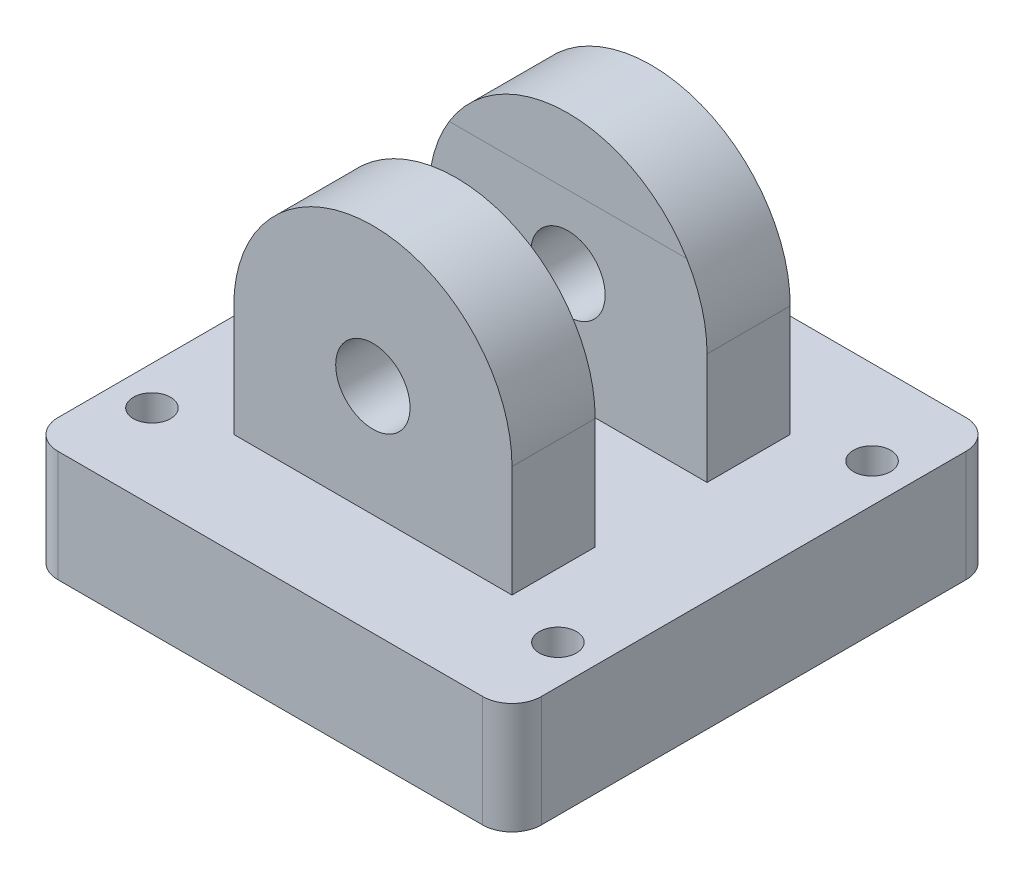
SolidWorks part; units mm, degrees
ref_plane "Front Plane" through (0, 0, 0) normal (0, 0, 1) x (1, 0, 0)
ref_plane "Top Plane" through (0, 0, 0) normal (0, 1, 0) x (1, 0, 0)
ref_plane "Right Plane" through (0, 0, 0) normal (1, 0, 0) x (0, 0, -1)
sketch "Sketch1" plane through (0, 0, 0) normal (0, 1, 0) x (1, 0, 0)
  line L1 (-82.5, 82.5) -> (82.5, 82.5)
  line L2 (-82.5, 82.5) -> (-82.5, -82.5)
  line L3 (-82.5, -82.5) -> (82.5, -82.5)
  line L4 (82.5, 82.5) -> (82.5, -82.5)
  line L5 (-82.5, 82.5) -> (82.5, -82.5) construction
  line L6 (-82.5, -82.5) -> (82.5, 82.5) construction
  point P0 (0, 0)
extrude "Boss-Extrude1" add sketch "Sketch1" along normal blind 38
sketch "Sketch2" plane through (0, 38, 0) normal (0, 1, 0) x (1, 0, 0)
  line L1 (-47.5, 47.5) -> (47.5, 47.5)
  line L2 (-47.5, 47.5) -> (-47.5, -47.5)
  line L3 (-47.5, -47.5) -> (47.5, -47.5)
  line L4 (47.5, 47.5) -> (47.5, -47.5)
  line L5 (-47.5, 47.5) -> (47.5, -47.5) construction
  line L6 (-47.5, -47.5) -> (47.5, 47.5) construction
  point P0 (0, 0)
extrude "Boss-Extrude2" add sketch "Sketch2" along normal blind 38
sketch "Sketch3" plane through (0, 0, -47.5) normal (0, 0, -1) x (-1, 0, 0)
  line L0 (-47.5, 76) -> (47.5, 76)
  arc A0 (-47.5, 76) -> (47.5, 76) centre (0, 76) cw
extrude "Boss-Extrude4" add sketch "Sketch3" against normal blind 95
sketch "Sketch5" plane through (0, 0, -47.5) normal (0, 0, -1) x (-1, 0, 0)
  circle A0 centre (0, 76) radius 12.7
extrude "Cut-Extrude1" cut sketch "Sketch5" against normal through all
sketch "Sketch7" plane through (47.5, 0, 0) normal (1, 0, 0) x (0, 0, -1)
  line L0 (0, 38) -> (19, 38)
  line L1 (-82.5, 38) -> (82.5, 38) construction
  line L2 (-47.5, 38) -> (47.5, 38) construction
sketch "Sketch8" plane through (82.5, 0, 0) normal (1, 0, 0) x (0, 0, -1)
  line L0 (19.102, 38) -> (19.102, 100.7488)
  line L1 (-82.5, 38) -> (82.5, 38) construction
  line L2 (19.102, 100.7488) -> (19.102, 123.5)
  line L3 (47.5, 123.5) -> (-47.5, 123.5) construction
  line L4 (19.102, 123.5) -> (19, 123.5)
  line L5 (19, 123.5) -> (-19, 123.5)
  line L6 (0, 123.5) -> (0, 38) construction
  line L7 (-19.102, 100.7488) -> (-19.102, 123.5)
  line L8 (-19.102, 38) -> (-19.102, 100.7488)
  line L9 (-19.102, 38) -> (19.102, 38)
extrude "Cut-Extrude2" cut sketch "Sketch8" against normal through all and the other way through all
fillet "Fillet1" radius 10 1 edges at (82.5, 19, 82.5)
fillet "Fillet2" radius 10 3 edges at (-82.5, 19, 82.5) (-82.5, 19, -82.5) (82.5, 19, -82.5)
sketch "Sketch9" plane through (0, 0, 0) normal (0, -1, 0) x (1, 0, 0)
  circle A0 centre (0, 0) radius 26
extrude "Cut-Extrude3" cut sketch "Sketch9" against normal blind 36.83
sketch "Sketch10" plane through (0, 0, 0) normal (0, -1, 0) x (1, 0, 0)
  circle A0 centre (0, 0) radius 69.85
  circle A1 centre (0, 0) radius 76.2
extrude "Cut-Extrude4" cut sketch "Sketch10" against normal blind 10
sketch "Sketch11" plane through (0, 0, -82.5) normal (0, 0, -1) x (-1, 0, 0)
  line L0 (-72.5, 19) -> (69.584, 19) construction
  line L1 (-72.5, 38) -> (-72.5, 0) construction
hole_wizard "1/2-14 NPSM Tapped Hole1" positions "3DSketch1" profile "Sketch12" tap size "1/2-14 NPSM" standard "ANSI Inch"
sketch3d "3DSketch1"
  line L0 (72.5, 19, -82.5) -> (-69.584, 19, -82.5) construction
  point P0 (-0.9389, 19, -82.5)
sketch "Sketch12" plane through (-0.9389, 19, -82.5) normal (1, 0, 0) x (0, 1, 0)
  line L0 (0, 0) -> (0, 69.2003)
  line L1 (0, 69.2003) -> (9.4869, 63.5)
  line L2 (9.4869, 63.5) -> (9.4869, 1.6002)
  line L3 (9.4869, 1.6002) -> (11.0871, 0)
  line L5 (11.0871, 0) -> (0, 0)
  line L6 (-9.4869, 1.6002) -> (-11.0871, 0) construction
  line L10 (0, 69.2003) -> (-9.4869, 63.5) construction
  line L11 (0, -6.35) -> (0, 107.95) construction
  dimension "Tap Drill Dia." = 18.9738
  dimension "Tap Drill Depth" = 63.5
  dimension "Near C'Sink Dia." = 22.1742
  dimension "Near C'Sink Angle" = 90
  dimension "Drill Angle" = 118
cosmetic thread "Hole Thread1" parameters "D1"=41.81, "D2"=20.9042
sketch "Sketch13" plane through (0, 0, 0) normal (0, -1, 0) x (1, 0, 0)
  line L0 (0, -50.5) -> (0, -82.5)
  line L2 (72.5, -82.5) -> (-69.584, -82.5) construction
  circle A0 centre (0, -50.5) radius 6.35
  dimension "D1" = 32
extrude "Cut-Extrude5" cut sketch "Sketch13" against normal blind 25 contours A0
sketch "Sketch14" plane through (0, 0, 0) normal (0, -1, 0) x (1, 0, 0)
  line L1 (-69.3018, 53.631) -> (69.3018, 53.631) construction
  line L2 (-69.3018, 53.631) -> (-69.3018, -53.631) construction
  line L3 (-69.3018, -53.631) -> (69.3018, -53.631) construction
  line L4 (69.3018, 53.631) -> (69.3018, -53.631) construction
  line L5 (-69.3018, 53.631) -> (69.3018, -53.631) construction
  line L6 (-69.3018, -53.631) -> (69.3018, 53.631) construction
  circle A0 centre (0, 0) radius 87.63 construction
  circle A1 centre (-69.3018, 53.631) radius 6.35
  circle A2 centre (-69.3018, -53.631) radius 6.35
  circle A3 centre (69.3018, -53.631) radius 6.35
  circle A5 centre (69.3018, 53.631) radius 6.35
extrude "Cut-Extrude7" cut sketch "Sketch14" against normal through all
